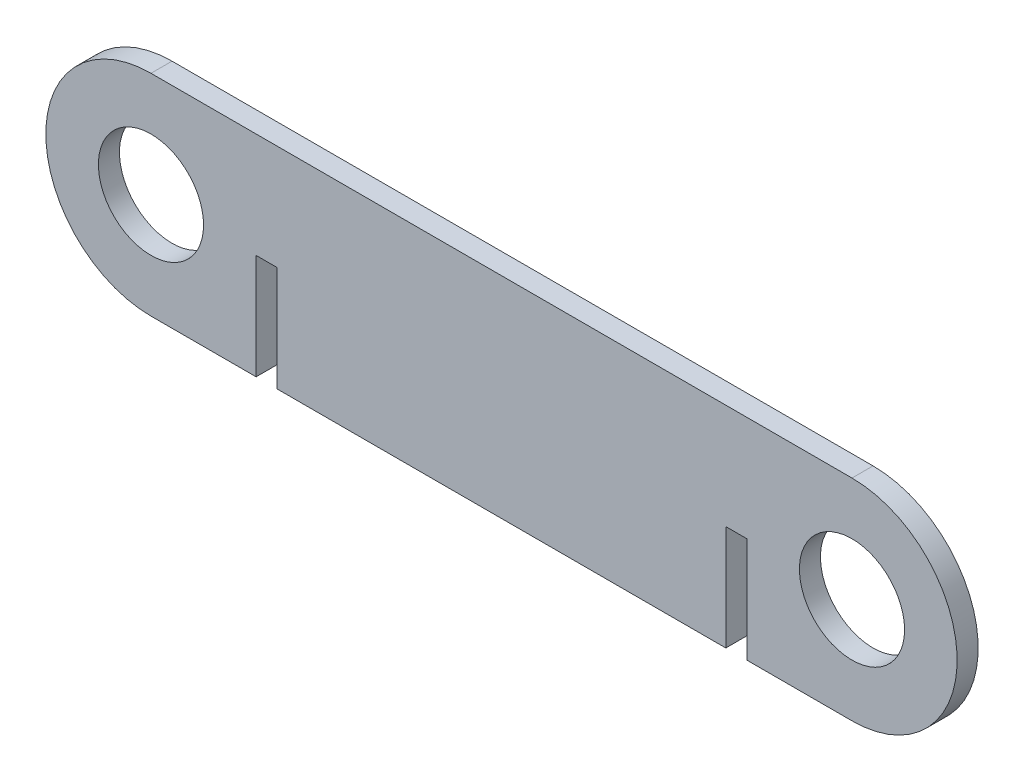
SolidWorks part; units mm, degrees
ref_plane "Front Plane" through (0, 0, 0) normal (0, 0, 1) x (1, 0, 0)
ref_plane "Top Plane" through (0, 0, 0) normal (0, 1, 0) x (1, 0, 0)
ref_plane "Right Plane" through (0, 0, 0) normal (1, 0, 0) x (0, 0, -1)
sketch "Sketch1" plane through (0, 0, 0) normal (0, 0, 1) x (1, 0, 0)
  line L0 (10.4552, 14.1145) -> (110.4552, 14.1145) construction
  line L1 (10.4552, 29.1145) -> (110.4552, 29.1145)
  line L2 (10.4552, -0.8855) -> (110.4552, -0.8855)
  arc A0 (10.4552, 29.1145) -> (10.4552, -0.8855) centre (10.4552, 14.1145) ccw
  arc A1 (110.4552, -0.8855) -> (110.4552, 29.1145) centre (110.4552, 14.1145) ccw
  point P2 (60.4552, 14.1145)
  dimension "D2" = 15
  dimension "D1" = 100
extrude "Boss-Extrude1" add sketch "Sketch1" along normal blind 3
sketch "Sketch2" plane through (0, 0, 3) normal (0, 0, 1) x (1, 0, 0)
  line L0 (10.4552, -0.8855) -> (110.4552, -0.8855) construction
  line L1 (25.4552, -0.8855) -> (28.4552, -0.8855)
  line L2 (25.4552, -0.8855) -> (25.4552, 14.1145)
  line L3 (25.4552, 14.1145) -> (28.4552, 14.1145)
  line L4 (28.4552, -0.8855) -> (28.4552, 14.1145)
  line L5 (60.4552, -0.8855) -> (60.4552, 38.9386) construction
  line L6 (92.4552, -0.8855) -> (92.4552, 14.1145)
  line L7 (95.4552, 14.1145) -> (92.4552, 14.1145)
  line L8 (95.4552, -0.8855) -> (95.4552, 14.1145)
  line L9 (95.4552, -0.8855) -> (92.4552, -0.8855)
  arc A0 (10.4552, 29.1145) -> (10.4552, -0.8855) centre (10.4552, 14.1145) ccw construction
  dimension "D1" = 3
  dimension "D2" = 15
  dimension "D3" = 15
extrude "Cut-Extrude1" cut sketch "Sketch2" against normal blind 3
sketch "Sketch3" plane through (0, 0, 3) normal (0, 0, 1) x (1, 0, 0)
  circle A0 centre (10.4552, 14.1145) radius 7.5
  circle A1 centre (110.4552, 14.1145) radius 7.5
  dimension "D1" = 15
  dimension "D2" = 15
extrude "Cut-Extrude2" cut sketch "Sketch3" against normal blind 3
